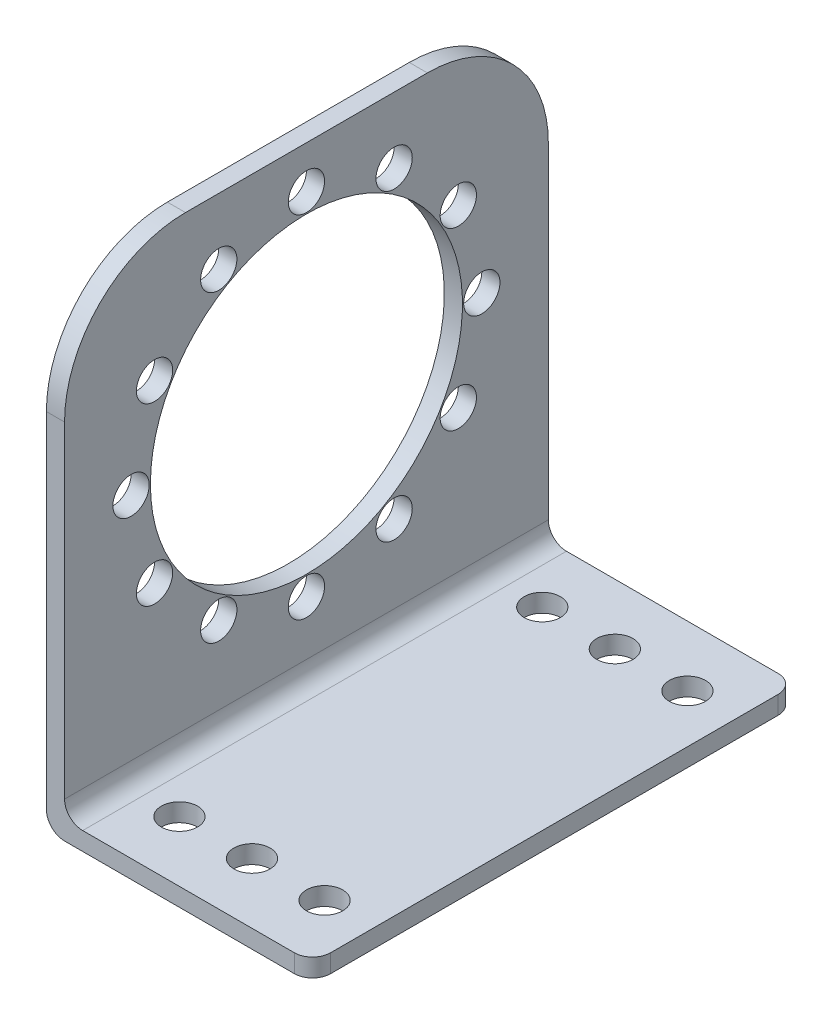
SolidWorks part; units mm, degrees
material "Cast Carbon Steel"
ref_plane "Front Plane" through (0, 0, 0) normal (0, 0, 1) x (1, 0, 0)
ref_plane "Top Plane" through (0, 0, 0) normal (0, 1, 0) x (1, 0, 0)
ref_plane "Right Plane" through (0, 0, 0) normal (1, 0, 0) x (0, 0, -1)
sketch "Sketch1" plane through (0, 0, 0) normal (0, 1, 0) x (1, 0, 0)
  line L0 (0, 0) -> (1.5, 0)
  line L1 (1.5, 0) -> (1.5, -40)
  line L2 (1.5, -40) -> (0, -40)
  line L3 (0, -40) -> (0, 0)
extrude "Boss-Extrude1" add sketch "Sketch1" along normal blind 40
sketch "Sketch2" plane through (1.5, 0, 0) normal (1, 0, 0) x (0, 0, -1)
  line L0 (-40, 0) -> (-40, 1.5)
  line L1 (-40, 40) -> (-40, 0) construction
  line L2 (-40, 0) -> (0, 0) construction
  line L3 (-40, 1.5) -> (0, 1.5)
  line L4 (0, 1.5) -> (0, 0)
  line L5 (0, 0) -> (-40, 0)
extrude "Boss-Extrude2" add sketch "Sketch2" along normal blind 20.5
sketch "Sketch3" plane through (0, 1.5, 0) normal (0, 1, 0) x (1, 0, 0)
  line L0 (22, 0) -> (22, -5)
  line L1 (22, 0) -> (22, -40) construction
  line L2 (6, -5) -> (6, -35)
  line L3 (6, -5) -> (12, -5)
  line L4 (22, -5) -> (18, -5)
  line L5 (12, -5) -> (12, -35)
  line L6 (18, -5) -> (18, -35)
  circle A0 centre (18, -5) radius 1.5
  circle A1 centre (12, -5) radius 1.5
  circle A2 centre (6, -5) radius 1.5
  circle A3 centre (6, -35) radius 1.5
  circle A4 centre (12, -35) radius 1.5
  circle A5 centre (18, -35) radius 1.5
extrude "Cut-Extrude1" cut sketch "Sketch3" against normal blind 20.5
fillet "Fillet5" radius 1.5 1 edges at (0, 0, 20)
fillet "Fillet6" radius 1.5 1 edges at (1.5, 1.5, 20)
fillet "Fillet7" radius 10 1 edges at (0.75, 40, 40)
fillet "Fillet8" radius 10 1 edges at (0.75, 40, 0)
sketch "Sketch6" plane through (1.5, 0, 0) normal (1, 0, 0) x (0, 0, -1)
  line L0 (-20, 3) -> (-20, 22)
  line L1 (-40, 3) -> (0, 3) construction
  circle A13 centre (-20, 22) radius 14.5
  circle A14 centre (-20, 36.5) radius 1.5
  circle A15 centre (-12.75, 34.5574) radius 1.5
  circle A16 centre (-7.4426, 29.25) radius 1.5
  circle A17 centre (-5.5, 22) radius 1.5
  circle A18 centre (-7.4426, 14.75) radius 1.5
  circle A19 centre (-12.75, 9.4426) radius 1.5
  circle A20 centre (-20, 7.5) radius 1.5
  circle A21 centre (-27.25, 9.4426) radius 1.5
  circle A22 centre (-32.5574, 14.75) radius 1.5
  circle A23 centre (-34.5, 22) radius 1.5
  circle A24 centre (-32.5574, 29.25) radius 1.5
  circle A25 centre (-27.25, 34.5574) radius 1.5
  point P32 (-20, 19)
  point P33 (-20, 22)
  dimension "D1" = 12
fillet "Fillet9" radius 1.5 1 edges at (22, 0.75, 40)
fillet "Fillet10" radius 1.5 1 edges at (22, 0.75, 0)
extrude "Cut-Extrude2" cut sketch "Sketch6" against normal blind 4 contours A24 | A25 | A14 | A15 | A16 | A17 | A18 | A19 | A20 | A21 | A22 | A23
sketch "Sketch7" plane through (0, 0, 0) normal (-1, 0, 0) x (0, 0, 1)
  line L0 (20, 1.5) -> (20, 22)
  line L1 (0, 1.5) -> (40, 1.5) construction
  circle A0 centre (20, 22) radius 12.9
extrude "Cut-Extrude5" cut sketch "Sketch7" against normal blind 4
